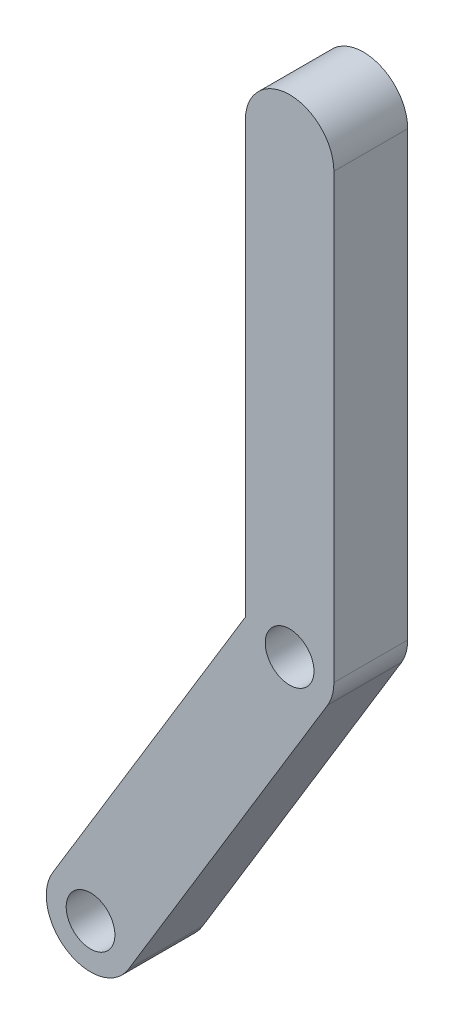
SolidWorks part; units mm, degrees
ref_plane "Ebene vorne" through (0, 0, 0) normal (0, 0, 1) x (1, 0, 0)
ref_plane "Ebene oben" through (0, 0, 0) normal (0, 1, 0) x (1, 0, 0)
ref_plane "Ebene rechts" through (0, 0, 0) normal (1, 0, 0) x (0, 0, -1)
sketch "Skizze1" plane through (0, 0, 0) normal (0, 0, 1) x (1, 0, 0)
  line L0 (0, 0) -> (-13.4881, -22.2277) construction
  line L1 (0, 0) -> (0, 30) construction
  line L2 (-13.4881, -22.2277) -> (21.9737, -22.2277) construction
  line L4 (-2.5441, 1.5898) -> (-16.0322, -20.638)
  line L5 (-3, 30) -> (-3, 0.8385)
  line L6 (2.5849, -1.5226) -> (-10.9032, -23.7503)
  line L7 (3, 30) -> (3, 0)
  circle A0 centre (0, 30) radius 3
  circle A1 centre (0, 0) radius 3
  circle A2 centre (-13.4881, -22.2277) radius 3
  circle A3 centre (-13.4881, -22.2277) radius 1.65
  circle A4 centre (0, 0) radius 1.65
  dimension "D4" = 6
  dimension "D5" = 6
  dimension "D6" = 3.3
  dimension "D7" = 3.3
  dimension "D8" = 6
  dimension "D1" = 58.75
  dimension "D2" = 26
  dimension "D3" = 30
extrude "Aufsatz-Linear austragen1" add sketch "Skizze1" along normal blind 5
